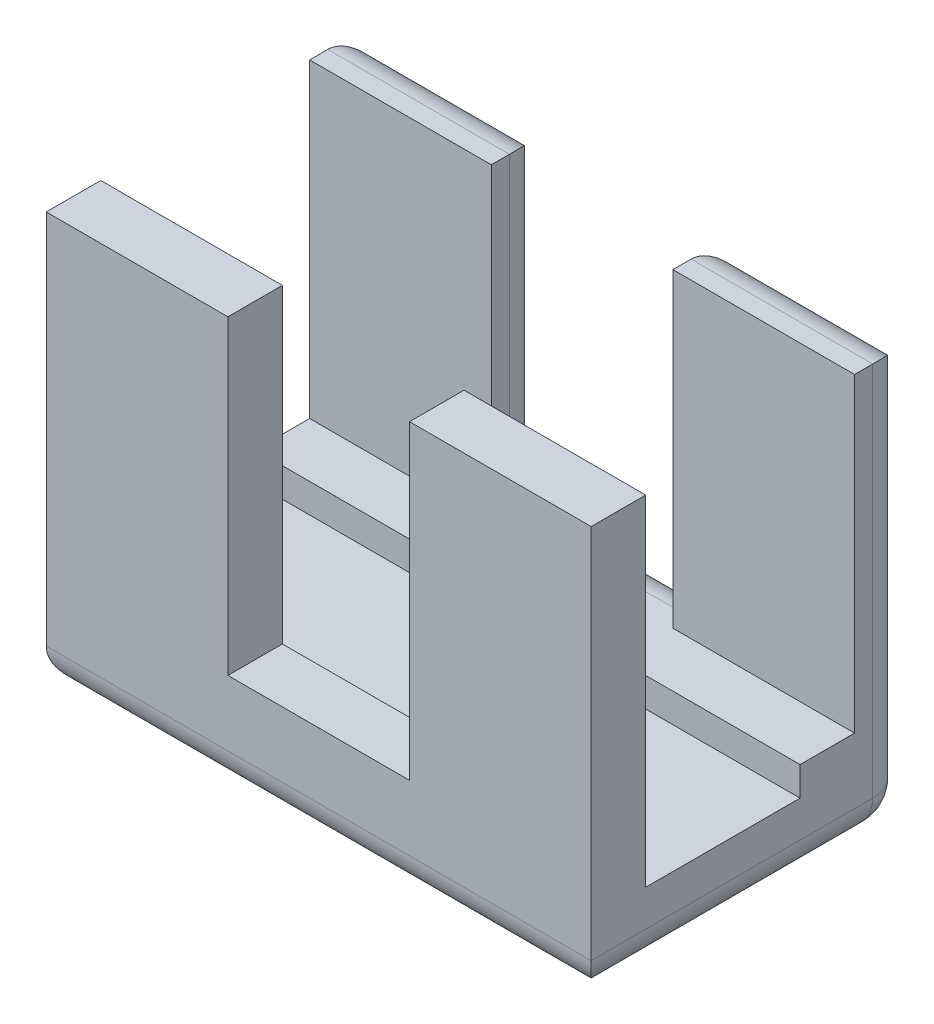
SolidWorks part; units mm, degrees
ref_plane "Front Plane" through (0, 0, 0) normal (0, 0, 1) x (1, 0, 0)
ref_plane "Top Plane" through (0, 0, 0) normal (0, 1, 0) x (1, 0, 0)
ref_plane "Right Plane" through (0, 0, 0) normal (1, 0, 0) x (0, 0, -1)
sketch "Sketch1" plane through (0, 0, 0) normal (0, 1, 0) x (1, 0, 0)
  line L1 (0, 0) -> (30, 0)
  line L2 (0, 0) -> (0, 17.5)
  line L3 (0, 17.5) -> (30, 17.5)
  line L4 (30, 0) -> (30, 17.5)
  dimension "D1" = 30
  dimension "D2" = 17.5
extrude "Boss-Extrude1" add sketch "Sketch1" along normal blind 4
sketch "Sketch2" plane through (0, 4, 0) normal (0, 1, 0) x (1, 0, 0)
  line L0 (30, 0) -> (30, 17.5) construction
  line L1 (0, 17.5) -> (30, 17.5)
  line L2 (0, 17.5) -> (0, 11.5)
  line L3 (0, 11.5) -> (30, 11.5)
  line L4 (30, 17.5) -> (30, 11.5)
  dimension "D1" = 6
extrude "Boss-Extrude2" add sketch "Sketch2" along normal blind 1.601
sketch "Sketch3" plane through (0, 4, 0) normal (0, 1, 0) x (1, 0, 0)
  line L1 (0, 0) -> (10, 0)
  line L2 (0, 0) -> (0, 3)
  line L3 (0, 3) -> (10, 3)
  line L4 (10, 0) -> (10, 3)
  line L5 (30, 0) -> (20, 0)
  line L6 (30, 0) -> (30, 3)
  line L7 (30, 3) -> (20, 3)
  line L8 (20, 0) -> (20, 3)
  dimension "D1" = 10
  dimension "D2" = 3
extrude "Boss-Extrude3" add sketch "Sketch3" along normal blind 18.7
sketch "Sketch4" plane through (0, 5.601, 0) normal (0, 1, 0) x (1, 0, 0)
  line L1 (0, 17.5) -> (10, 17.5)
  line L2 (0, 17.5) -> (0, 14.5)
  line L3 (0, 14.5) -> (10, 14.5)
  line L4 (10, 17.5) -> (10, 14.5)
  line L5 (30, 17.5) -> (20, 17.5)
  line L6 (30, 17.5) -> (30, 14.5)
  line L7 (30, 14.5) -> (20, 14.5)
  line L8 (20, 17.5) -> (20, 14.5)
  dimension "D1" = 10
  dimension "D2" = 3
extrude "Boss-Extrude4" add sketch "Sketch4" along normal blind 17.099
sketch "Sketch5" plane through (0, 4, 0) normal (0, 1, 0) x (1, 0, 0)
  line L1 (10, 3) -> (20, 3)
  line L2 (10, 3) -> (10, 0)
  line L3 (10, 0) -> (20, 0)
  line L4 (20, 3) -> (20, 0)
extrude "Boss-Extrude5" add sketch "Sketch5" along normal blind 1.601
fillet "Fillet1" radius 2 11 edges at (30, 11.35, -17.5) (25, 22.7, -17.5) (20, 14.1505, -17.5) (15, 5.601, -17.5) (10, 14.1505, -17.5) (5, 22.7, -17.5) (0, 11.35, -17.5) (15, 0, 0) (30, 0, -8.75) (15, 0, -17.5) (0, 0, -8.75)
